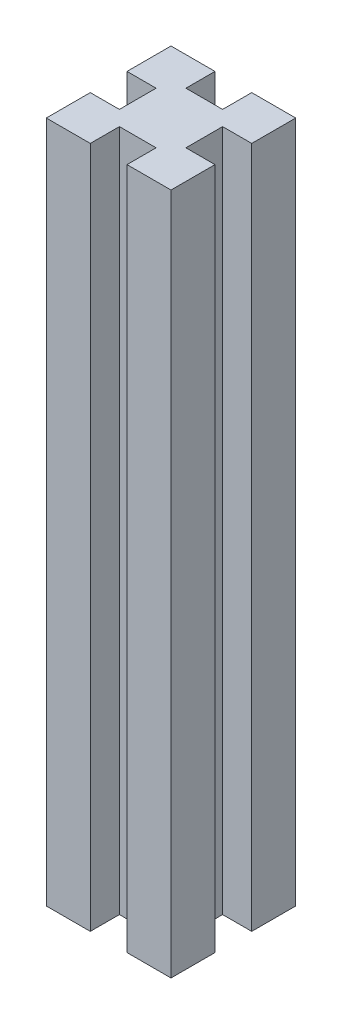
SolidWorks part; units mm, degrees
ref_plane "Front Plane" through (0, 0, 0) normal (0, 0, 1) x (1, 0, 0)
ref_plane "Top Plane" through (0, 0, 0) normal (0, 1, 0) x (1, 0, 0)
ref_plane "Right Plane" through (0, 0, 0) normal (1, 0, 0) x (0, 0, -1)
other "Configuration Table"
sketch "Sketch1" plane through (0, 0, 0) normal (0, 1, 0) x (1, 0, 0)
  line L5 (7.425, 4.1) -> (13.925, 4.1)
  line L6 (-13.925, 13.925) -> (-4.1, 13.925)
  line L10 (-13.925, 13.925) -> (-13.925, 4.1)
  line L11 (-13.925, -13.925) -> (-4.1, -13.925)
  line L12 (13.925, 13.925) -> (13.925, 4.1)
  line L13 (-13.925, 13.925) -> (13.925, -13.925) construction
  line L14 (-13.925, -13.925) -> (13.925, 13.925) construction
  line L15 (-4.1, 7.425) -> (4.1, 7.425)
  line L16 (-4.1, 7.425) -> (-4.1, 13.925)
  line L17 (-4.1, 13.925) -> (4.1, 13.925) construction
  line L18 (4.1, 7.425) -> (4.1, 13.925)
  line L19 (-4.1, 7.425) -> (0, 10.675) construction
  line L20 (-4.1, 13.925) -> (4.1, 7.425) construction
  line L21 (7.425, 4.1) -> (7.425, -4.1)
  line L22 (7.425, -4.1) -> (13.925, -4.1)
  line L23 (13.925, 4.1) -> (13.925, -4.1) construction
  line L24 (4.1, -7.425) -> (4.1, -13.925)
  line L25 (4.1, -7.425) -> (-4.1, -7.425)
  line L26 (-4.1, -7.425) -> (-4.1, -13.925)
  line L27 (4.1, -13.925) -> (-4.1, -13.925) construction
  line L28 (-7.425, -4.1) -> (-13.925, -4.1)
  line L29 (-7.425, -4.1) -> (-7.425, 4.1)
  line L30 (-7.425, 4.1) -> (-13.925, 4.1)
  line L31 (-13.925, -4.1) -> (-13.925, 4.1) construction
  line L32 (-13.925, 4.1) -> (-13.925, -4.1) construction
  line L33 (-13.925, -4.1) -> (-13.925, -13.925)
  line L34 (0, 10.675) -> (4.1, 13.925) construction
  line L35 (-4.1, 13.925) -> (4.1, 13.925) construction
  line L36 (4.1, 13.925) -> (13.925, 13.925)
  line L37 (13.925, 4.1) -> (13.925, -4.1) construction
  line L38 (13.925, -4.1) -> (13.925, -13.925)
  line L39 (-4.1, -13.925) -> (4.1, -13.925) construction
  line L40 (4.1, -13.925) -> (13.925, -13.925)
  point P0 (0, 0)
  point P5 (0, 10.675)
  point P11 (0, -7.425)
  point P26 (0, 0)
  dimension "D3" = 6.5
  dimension "D1" = 27.85
  dimension "D2" = 8.2
  dimension "D4" = 4
extrude "Boss-Extrude1" add sketch "Sketch1" along normal blind 152.4
equation "\"length\"= 6"
equation "\"D1@Boss-Extrude1\"=\"length\""
